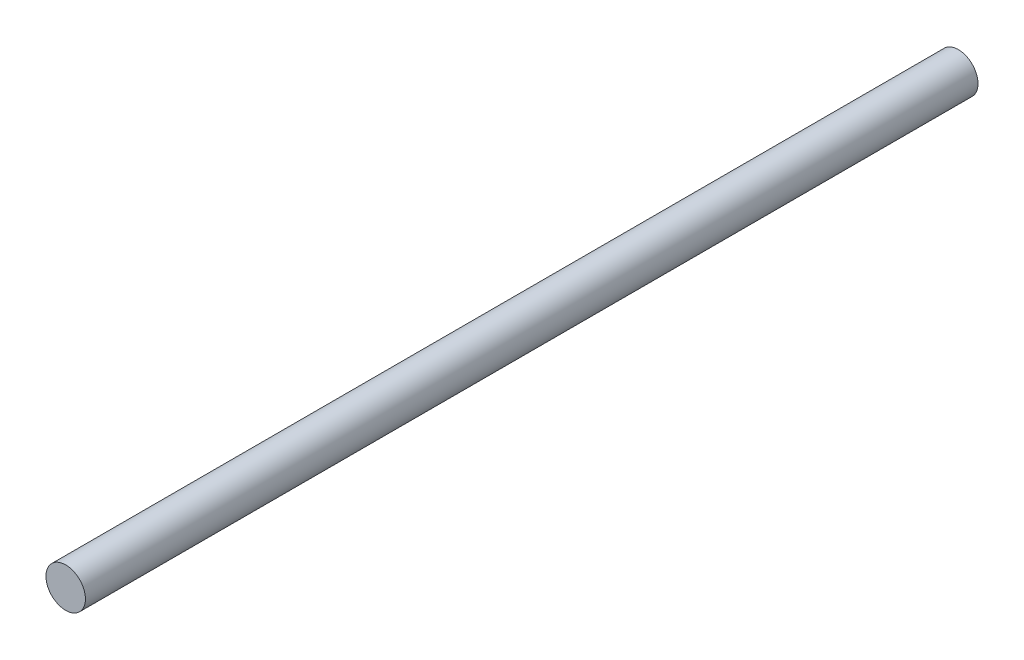
SolidWorks part; units mm, degrees
ref_plane "Front Plane" through (0, 0, 0) normal (0, 0, 1) x (1, 0, 0)
ref_plane "Top Plane" through (0, 0, 0) normal (0, 1, 0) x (1, 0, 0)
ref_plane "Right Plane" through (0, 0, 0) normal (1, 0, 0) x (0, 0, -1)
sketch "Sketch1" plane through (0, 0, 0) normal (0, 0, 1) x (1, 0, 0)
  circle A0 centre (0, 0) radius 4.8625
  dimension "D1" = 9.725
extrude "Boss-Extrude1" add sketch "Sketch1" along normal mid plane 220
